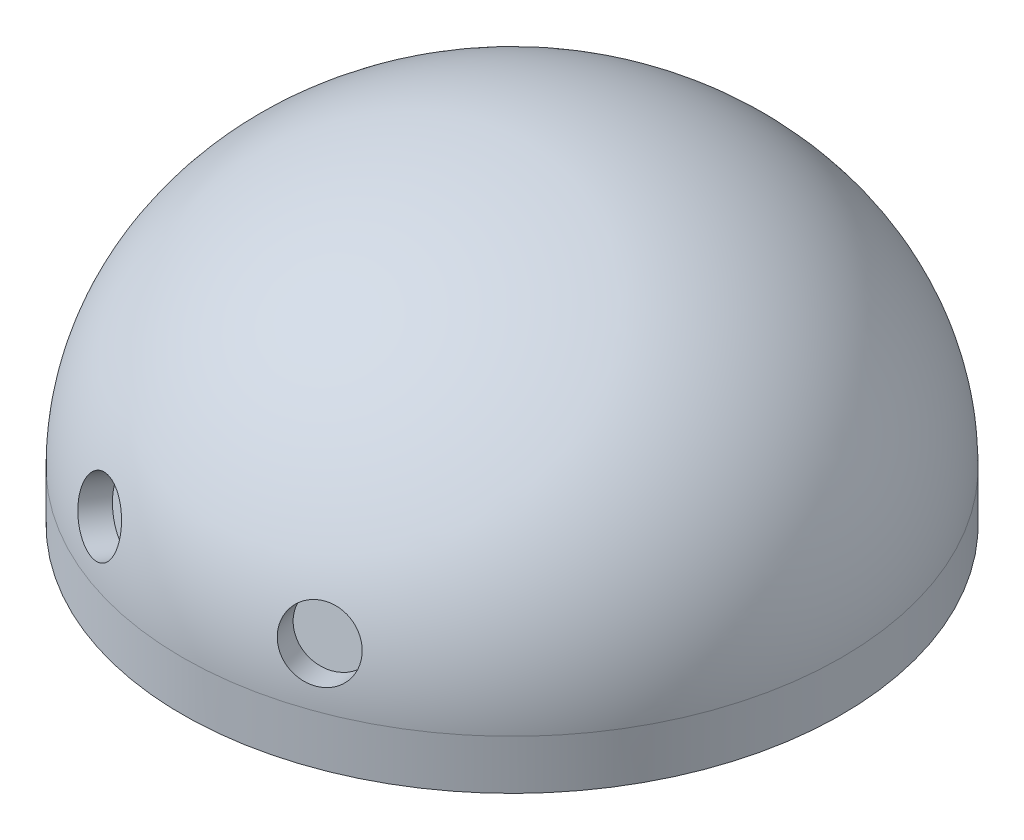
SolidWorks part; units mm, degrees
ref_plane "Plano frontal" through (0, 0, 0) normal (0, 0, 1) x (1, 0, 0)
ref_plane "Plano superior" through (0, 0, 0) normal (0, 1, 0) x (1, 0, 0)
ref_plane "Plano direito" through (0, 0, 0) normal (1, 0, 0) x (0, 0, -1)
sketch "Esboço4" plane through (0, 0, 0) normal (0, 0, 1) x (1, 0, 0)
  line L0 (0, 26.6774) -> (0, -22.5296) construction
  line L1 (0, 0) -> (0, 17)
  line L2 (0, 0) -> (20, 0)
  ellipse E0 centre (0, 0) end of major axis (-20, 0) minor radius 17 (20, 0) -> (0, 17) ccw
  dimension "D1" = 17
  dimension "D2" = 20
revolve "Casca da Cabeça" add sketch "Esboço4" angle 360 about L0
sketch "Esboço5" plane through (0, 0, 0) normal (0, -1, 0) x (1, 0, 0)
  circle A0 centre (0, 0) radius 20
  dimension "D1" = 40
extrude "Extensão da Cabeça" add sketch "Esboço5" along normal blind 3
sketch "Referencia XZ" plane through (0, 0, 0) normal (0, 1, 0) x (1, 0, 0)
  line L0 (0, 0) -> (0, -25) construction
  line L1 (0, 0) -> (16.0697, -19.1511) construction
  dimension "D1" = 25
  dimension "D2" = 25
  dimension "D3" = 40
ref_plane "Plano9" through (0, 0, 0) normal (-0.766, 0, 0.6428) x (0.6428, 0, 0.766)
sketch "Referencia ZY 1" plane through (0, 0, 0) normal (-0.766, 0, 0.6428) x (0.6428, 0, 0.766)
  line L0 (0, 0) -> (25, 0) construction
  line L1 (0, 0) -> (25, 0) construction
  line L2 (0, 0) -> (23.4923, 8.5505) construction
  dimension "D1" = 25
  dimension "D2" = 20
  dimension "D3" = 25
ref_plane "Plano10" through (0, 0, 0) normal (-1, 0, 0) x (0, 0, 1)
sketch "Referencia ZY 2" plane through (0, 0, 0) normal (-1, 0, 0) x (0, 0, 1)
  line L0 (0, 0) -> (25, 0) construction
  line L1 (0, 0) -> (23.4923, 8.5505) construction
  dimension "D1" = 25
  dimension "D2" = 25
  dimension "D3" = 20
ref_plane "Plano11" through (7.8201, 3.7885, 21.4857) normal (-0.3374, -0.1635, -0.9271) x (-0.9414, 0.0586, 0.3323)
sketch "Esboço23" plane through (7.8201, 3.7885, 21.4857) normal (-0.3374, -0.1635, -0.9271) x (-0.9414, 0.0586, 0.3323)
  circle A0 centre (0, 0) radius 2
  dimension "D1" = 4
extrude "Furo do Olho" cut sketch "Esboço23" along normal blind 5
mirror "Face Esquerda (Espelhar)" about plane through (0, 0, 0) normal (1, 0, 0) of "Furo do Olho"
